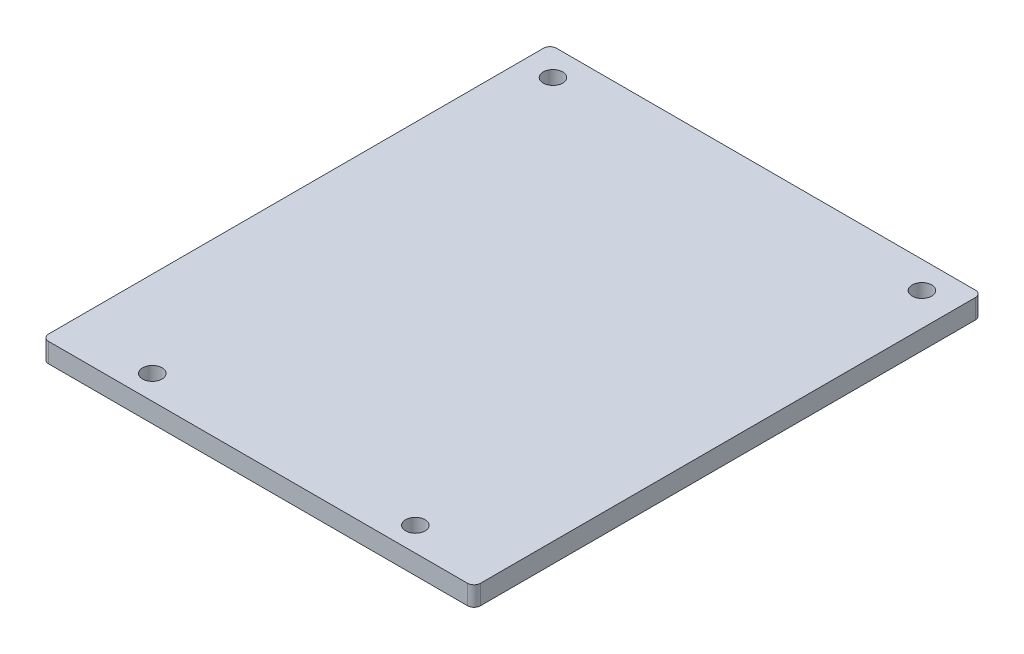
SolidWorks part; units mm, degrees
ref_plane "Front Plane" through (0, 0, 0) normal (0, 0, 1) x (1, 0, 0)
ref_plane "Top Plane" through (0, 0, 0) normal (0, 1, 0) x (1, 0, 0)
ref_plane "Right Plane" through (0, 0, 0) normal (1, 0, 0) x (0, 0, -1)
sketch "Sketch1" plane through (0, 0, 0) normal (0, 1, 0) x (1, 0, 0)
  line L1 (0, 0) -> (66.421, 0)
  line L2 (0, 0) -> (0, 78.105)
  line L3 (0, 78.105) -> (66.421, 78.105)
  line L4 (66.421, 0) -> (66.421, 78.105)
  dimension "D1" = 66.421
  dimension "D2" = 78.105
extrude "Boss-Extrude1" add sketch "Sketch1" along normal blind 3
sketch "Sketch2" plane through (0, 3, 0) normal (0, 1, 0) x (1, 0, 0)
  line L0 (0, 73.936) -> (4.628, 73.936)
  line L1 (0, 78.105) -> (0, 0) construction
  line L2 (4.628, 73.936) -> (4.628, 78.105)
  line L3 (66.421, 78.105) -> (0, 78.105) construction
  line L4 (4.628, 73.936) -> (61.376, 73.936)
  line L5 (0, 3.708) -> (13.233, 3.708)
  line L6 (13.233, 3.708) -> (13.233, 0)
  line L7 (0, 0) -> (66.421, 0) construction
  line L8 (13.233, 3.708) -> (53.695, 3.708)
  circle A0 centre (4.628, 73.936) radius 1.5
  circle A1 centre (61.376, 73.936) radius 1.5
  circle A2 centre (13.233, 3.708) radius 1.5
  circle A3 centre (53.695, 3.708) radius 1.5
  dimension "D7" = 3
  dimension "D8" = 3
  dimension "D9" = 3
  dimension "D10" = 3
  dimension "D1" = 4.628
  dimension "D2" = 4.169
  dimension "D3" = 56.748
  dimension "D4" = 13.233
  dimension "D5" = 3.708
  dimension "D6" = 40.462
extrude "Cut-Extrude1" cut sketch "Sketch2" against normal blind 3 contours A0 | A1 | A2 | A3
fillet "Fillet1" radius 1 4 edges at (0, 1.5, 0) (66.421, 1.5, 0) (66.421, 1.5, -78.105) (0, 1.5, -78.105)
